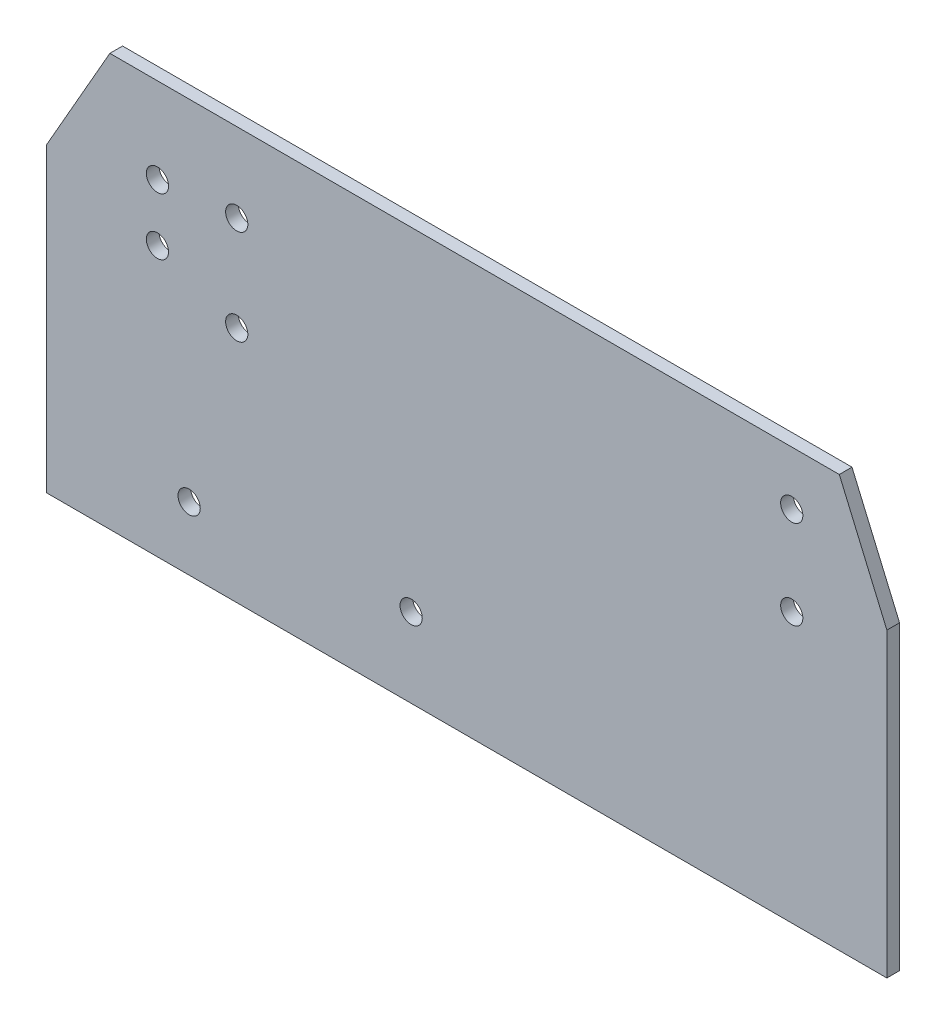
SolidWorks part; units mm, degrees
ref_plane "前视基准面" through (0, 0, 0) normal (0, 0, 1) x (1, 0, 0)
ref_plane "上视基准面" through (0, 0, 0) normal (0, 1, 0) x (1, 0, 0)
ref_plane "右视基准面" through (0, 0, 0) normal (1, 0, 0) x (0, 0, -1)
other "Configuration Table"
sketch "草图1" plane through (0, 0, 0) normal (0, 0, 1) x (1, 0, 0)
  line L0 (-115, -25) -> (150, -25)
  line L1 (150, -25) -> (150, 70)
  line L2 (150, 70) -> (135, 105)
  line L3 (135, 105) -> (-95, 105)
  line L4 (-95, 105) -> (-115, 70)
  line L5 (-115, 70) -> (-115, -25)
  circle A0 centre (0, 0) radius 3.5
  circle A1 centre (-80, 60) radius 3.5
  circle A2 centre (120, 60) radius 3.5
  circle A3 centre (-70, -5) radius 3.5
  circle A4 centre (-55, 50) radius 3.5
  circle A5 centre (-55, 80) radius 3.5
  circle A6 centre (120, 88) radius 3.5
  circle A7 centre (-80, 78) radius 3.5
extrude "凸台-拉伸1" add sketch "草图1" along normal mid plane 4
